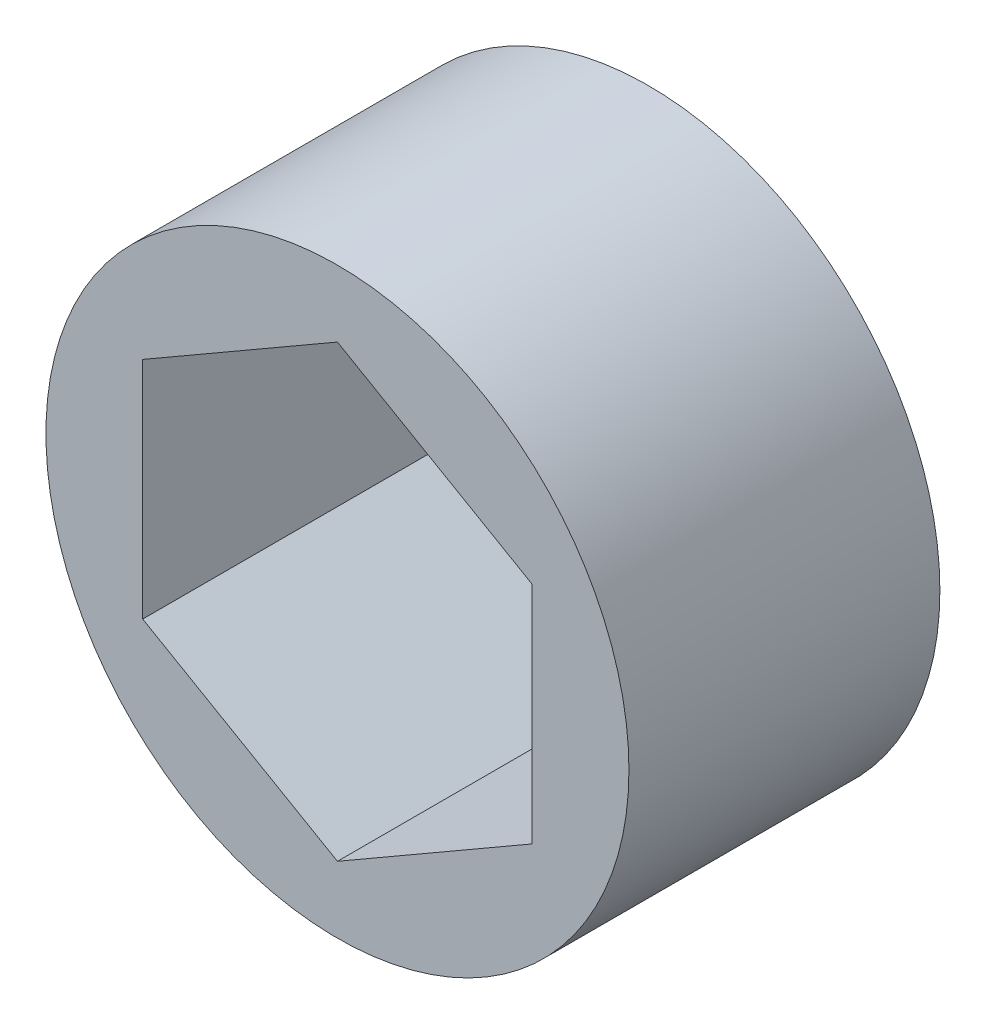
SolidWorks part; units mm, degrees
ref_plane "Front Plane" through (0, 0, 0) normal (0, 0, 1) x (1, 0, 0)
ref_plane "Top Plane" through (0, 0, 0) normal (0, 1, 0) x (1, 0, 0)
ref_plane "Right Plane" through (0, 0, 0) normal (1, 0, 0) x (0, 0, -1)
sketch "Sketch1" plane through (0, 0, 0) normal (0, 0, 1) x (1, 0, 0)
  line L1 (6.3627, 3.6735) -> (0, 7.347)
  line L2 (0, 7.347) -> (-6.3627, 3.6735)
  line L3 (-6.3627, 3.6735) -> (-6.3627, -3.6735)
  line L4 (-6.3627, -3.6735) -> (0, -7.347)
  line L5 (0, -7.347) -> (6.3627, -3.6735)
  line L6 (6.3627, -3.6735) -> (6.3627, 3.6735)
  circle A0 centre (0, 0) radius 6.3627 construction
  circle A1 centre (0, 0) radius 9.525
  dimension "D1" = 12.7254
  dimension "D2" = 19.05
extrude "Boss-Extrude1" add sketch "Sketch1" along normal mid plane 10.16
